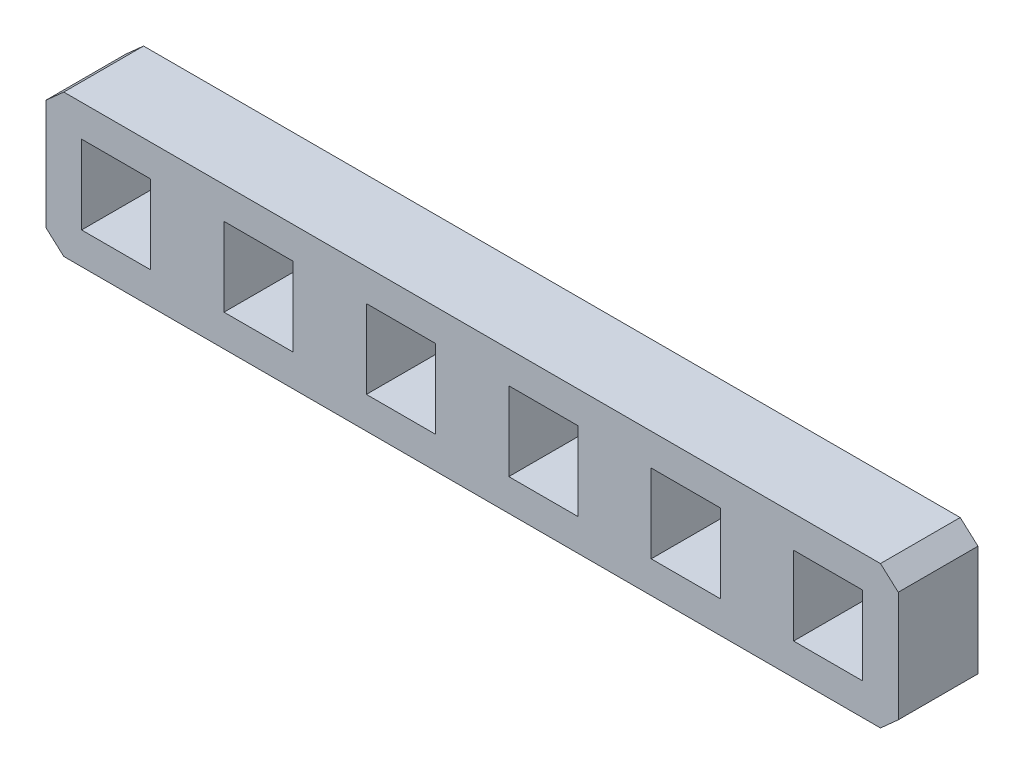
SolidWorks part; units mm, degrees
ref_plane "Piano frontale" through (0, 0, 0) normal (0, 0, 1) x (1, 0, 0)
ref_plane "Piano superiore" through (0, 0, 0) normal (0, 1, 0) x (1, 0, 0)
ref_plane "Piano destro" through (0, 0, 0) normal (1, 0, 0) x (0, 0, -1)
sketch "Schizzo1" plane through (0, 0, 0) normal (0, 0, 1) x (1, 0, 0)
  line L0 (-18.05, -2.7625) -> (-18.05, 2.7625)
  line L1 (-30.55, 3.8813) -> (-30.55, -3.8813)
  line L2 (29.3, 3.8813) -> (29.3, -3.8813)
  line L4 (-29.3, 5) -> (-30.55, 3.8813)
  line L5 (28.05, -5) -> (29.3, -3.8813)
  line L6 (28.05, 5) -> (29.3, 3.8813)
  line L7 (-28.05, -2.7625) -> (-23.2, -2.7625)
  line L8 (-28.05, -2.7625) -> (-28.05, 2.7625)
  line L9 (-29.3, -5) -> (-30.55, -3.8813)
  line L10 (-23.2, -2.7625) -> (-23.2, 2.7625)
  line L11 (-28.05, -2.7625) -> (-23.2, 0) construction
  line L12 (-28.05, 0) -> (-23.2, -2.7625) construction
  line L13 (-18.05, -2.7625) -> (-13.2, -2.7625)
  line L14 (-13.2, -2.7625) -> (-13.2, 2.7625)
  line L15 (-8.05, -2.7625) -> (-8.05, 2.7625)
  line L16 (-8.05, -2.7625) -> (-3.2, -2.7625)
  line L17 (-3.2, -2.7625) -> (-3.2, 2.7625)
  line L18 (1.95, -2.7625) -> (1.95, 2.7625)
  line L19 (1.95, -2.7625) -> (6.8, -2.7625)
  line L20 (6.8, -2.7625) -> (6.8, 2.7625)
  line L21 (11.95, -2.7625) -> (11.95, 2.7625)
  line L22 (11.95, -2.7625) -> (16.8, -2.7625)
  line L23 (16.8, -2.7625) -> (16.8, 2.7625)
  line L24 (21.95, -2.7625) -> (21.95, 2.7625)
  line L25 (21.95, -2.7625) -> (26.8, -2.7625)
  line L26 (26.8, -2.7625) -> (26.8, 2.7625)
  line L27 (21.95, 2.7625) -> (26.8, 2.7625)
  line L28 (11.95, 2.7625) -> (16.8, 2.7625)
  line L33 (-29.3, -5) -> (28.05, -5)
  line L35 (1.95, 2.7625) -> (6.8, 2.7625)
  line L36 (-8.05, 2.7625) -> (-3.2, 2.7625)
  line L37 (-18.05, 2.7625) -> (-13.2, 2.7625)
  line L38 (-28.05, 2.7625) -> (-23.2, 2.7625)
  line L39 (-29.3, 5) -> (28.05, 5)
  point P0 (-30.55, 0)
  point P1 (-25.625, -1.3813)
  point P2 (26.8, 0)
  point P3 (29.3, 0)
  dimension "D2" = 4.85
  dimension "D3" = 5.525
  dimension "D1" = 5.15
  dimension "D5" = 2.5
  dimension "D6" = 2.5
  dimension "D7" = 10
  dimension "D4" = 6
extrude "Estrusione-Estrusione2" add sketch "Schizzo1" along normal blind 5.6
equation "\"side\"= 65'hexagon side"
equation "\"joint whidth\"= 5"
equation "\"mat thickness\"= 5.6"
equation "\"kerf\"= 0.075"
equation "\"D2@Schizzo1\"= \"joint whidth\" - ( \"kerf\" * 2 )"
equation "\"D3@Schizzo1\"= \"mat thickness\" - \"kerf\""
equation "\"D1@Schizzo1\"= \"joint whidth\" + ( \"kerf\" * 2 )"
equation "\"D5@Schizzo1\"= \"joint whidth\" / 2"
equation "\"D6@Schizzo1\"= \"joint whidth\" / 2"
equation "\"D7@Schizzo1\"= \"joint whidth\" * 2"
